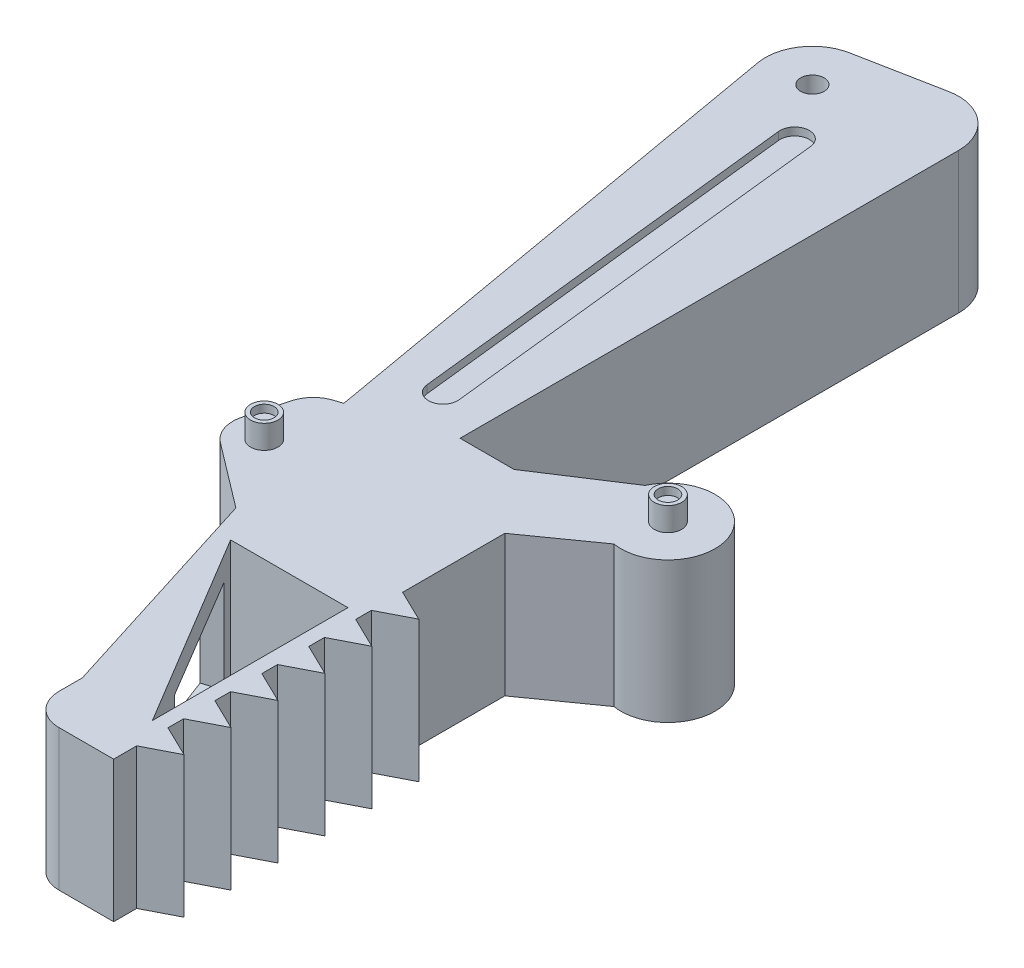
SolidWorks part; units mm, degrees
ref_plane "Front Plane" through (0, 0, 0) normal (0, 0, 1) x (1, 0, 0)
ref_plane "Top Plane" through (0, 0, 0) normal (0, 1, 0) x (1, 0, 0)
ref_plane "Right Plane" through (0, 0, 0) normal (1, 0, 0) x (0, 0, -1)
sketch "Sketch2" plane through (0, 0, 0) normal (0, 1, 0) x (1, 0, 0)
  line L0 (-39.564, -83.8329) -> (-42.63, -84.7998)
  line L1 (-39.564, -83.8329) -> (-51.8315, -13.8329)
  line L2 (-51.8315, -13.8329) -> (-28.269, -9.271)
  line L3 (-28.269, -9.271) -> (-28.269, -80.271)
  line L5 (-42.63, -84.7998) -> (-45.2405, -94.4517)
  line L6 (-28.269, -80.271) -> (-21.3637, -80.271)
  line L7 (-45.2405, -94.4517) -> (-34.8844, -102.3099)
  line L8 (-34.8844, -102.3099) -> (-25.889, -130.9295)
  line L9 (-25.889, -130.9295) -> (-25.889, -137.9295)
  line L10 (-25.889, -137.9295) -> (-14.889, -137.9295)
  line L11 (-14.889, -137.9295) -> (-14.889, -87.9295)
  line L12 (-14.889, -87.9295) -> (-6.7356, -82.1396)
  line L13 (-21.3637, -80.271) -> (-11.2267, -73.6707)
  arc A0 (-11.2267, -73.6707) -> (-6.7356, -82.1396) centre (-5.764, -76.1991) cw
  dimension "D1" = 70
  dimension "D3" = 24
  dimension "D4" = 13
  dimension "D5" = 30
  dimension "D6" = 7
  dimension "D7" = 11
  dimension "D8" = 50
  dimension "D9" = 10
extrude "Boss-Extrude1" add sketch "Sketch2" along normal mid plane 18
fillet "Fillet1" radius 6 2 edges at (-28.269, 0, 9.271) (-51.8315, 0, 13.8329)
fillet "Fillet2" radius 4 3 edges at (-25.889, 0, 137.9295) (-45.2405, 0, 94.4517) (-42.63, 0, 84.7998)
sketch "Sketch3" plane through (0, 9, 0) normal (0, 1, 0) x (1, 0, 0)
  line L1 (-14.889, -137.9295) -> (-14.889, -87.9295) construction
  line L3 (-14.889, -130.9866) -> (-14.889, -134.9866)
  line L4 (-14.889, -130.9866) -> (-10.8843, -132.9314)
  line L5 (-10.8843, -132.9314) -> (-14.889, -134.9866)
  dimension "D1" = 4
extrude "Boss-Extrude2" add sketch "Sketch3" against normal blind 18
pattern_linear "LPattern1" count 6 spacing 6 along (0, 0, -1) of "Boss-Extrude2"
sketch "Sketch4" plane through (0, 9, 0) normal (0, 1, 0) x (1, 0, 0)
  line L0 (-16.6831, -131.1835) -> (-16.6831, -106.1835)
  line L1 (-16.6831, -106.1835) -> (-31.6831, -106.1835)
  line L2 (-31.6831, -106.1835) -> (-16.6831, -131.1835)
  dimension "D1" = 15
  dimension "D2" = 25
extrude "Cut-Extrude1" cut sketch "Sketch4" against normal through all
sketch "Sketch5" plane through (-61.0137, 0, 19.1771) normal (-0.954, 0, 0.2998) x (0.2998, 0, 0.954)
  line L0 (94.1424, 6) -> (94.1424, -6)
  line L1 (94.1424, -6) -> (112.1424, -7.7906)
  line L2 (112.1424, -7.7906) -> (112.1424, 6.178)
  line L3 (112.1424, 6.178) -> (94.1424, 6)
  line L5 (87.1424, 9) -> (117.1424, 9) construction
  line L6 (117.1424, 9) -> (117.1424, -9) construction
  line L7 (87.1424, -9) -> (117.1424, -9) construction
  line L8 (87.1424, 9) -> (87.1424, -9) construction
  point P5 (112.1424, -0.8063)
  dimension "D1" = 3
  dimension "D2" = 5
  dimension "D3" = 3
  dimension "D4" = 7
extrude "Cut-Extrude2" cut sketch "Sketch5" against normal blind 8
sketch "Sketch6" plane through (0, 9, 0) normal (0, 1, 0) x (1, 0, 0)
  circle A1 centre (-44.9041, -18.6031) radius 1.5
  dimension "D1" = 3
extrude "Cut-Extrude3" cut sketch "Sketch6" against normal through all
sketch "Sketch7" plane through (0, 9, 0) normal (0, 1, 0) x (1, 0, 0)
  circle A0 centre (-40.6756, -92.8944) radius 1.75
  circle A1 centre (-5.764, -76.1991) radius 1.75
  dimension "D1" = 3.5
  dimension "D2" = 3.5
extrude "Boss-Extrude3" add sketch "Sketch7" along normal blind 3
sketch "Sketch9" plane through (0, 12, 0) normal (0, 1, 0) x (1, 0, 0)
  circle A2 centre (-40.6756, -92.8944) radius 1.25
  circle A3 centre (-40.6756, -92.8944) radius 1.25
  dimension "D1" = 0.5
extrude "Cut-Extrude4" cut sketch "Sketch9" against normal blind 1
sketch "Sketch10" plane through (0, 12, 0) normal (0, 1, 0) x (1, 0, 0)
  circle A2 centre (-5.764, -76.1991) radius 1.25
  circle A3 centre (-5.764, -76.1991) radius 1.25
  dimension "D1" = 0.5
extrude "Cut-Extrude5" cut sketch "Sketch10" against normal blind 1
sketch "Sketch11" plane through (0, 9, 0) normal (0, 1, 0) x (1, 0, 0)
  line L0 (-40.0254, -25.7401) -> (-34.4491, -76.2645) construction
  line L1 (-38.1706, -25.5354) -> (-32.5943, -76.0598)
  line L2 (-41.8802, -25.9448) -> (-36.3039, -76.4693)
  arc A0 (-38.1706, -25.5354) -> (-41.8802, -25.9448) centre (-40.0254, -25.7401) ccw
  arc A1 (-36.3039, -76.4693) -> (-32.5943, -76.0598) centre (-34.4491, -76.2645) ccw
  point P2 (-37.2372, -51.0023)
extrude "Cut-Extrude7" cut sketch "Sketch11" against normal blind 1
mirror "Mirror1" about plane through (0, 0, 0) normal (0, 1, 0) of "Cut-Extrude7", "Cut-Extrude5", "Cut-Extrude4", "Boss-Extrude3"
